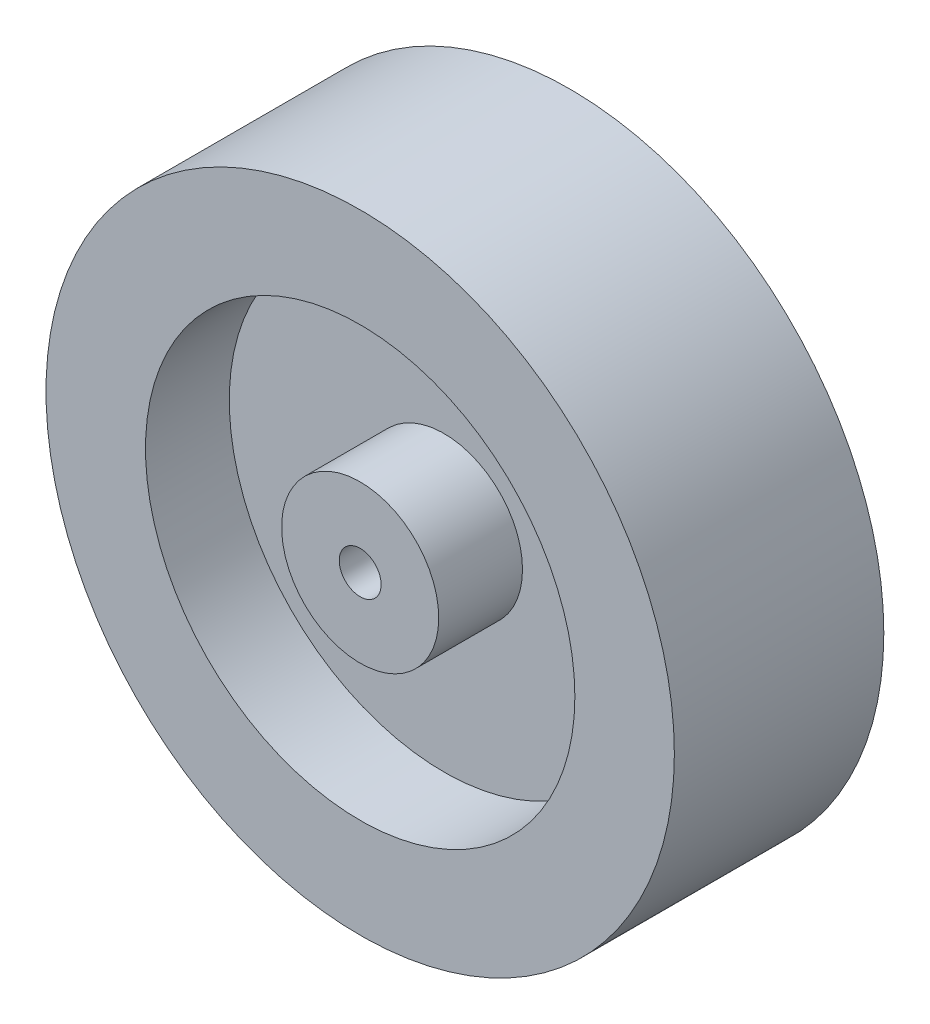
SolidWorks part; units mm, degrees
material "AISI 1020"
ref_plane "Plano frontal" through (0, 0, 0) normal (0, 0, 1) x (1, 0, 0)
ref_plane "Plano superior" through (0, 0, 0) normal (0, 1, 0) x (1, 0, 0)
ref_plane "Plano direito" through (0, 0, 0) normal (1, 0, 0) x (0, 0, -1)
sketch "Esboço1" plane through (0, 0, 0) normal (0, 0, 1) x (1, 0, 0)
  circle A0 centre (0, 0) radius 15
  circle A1 centre (0, 0) radius 1
  dimension "D1" = 30
  dimension "D2" = 2
extrude "Ressalto-extrusão1" add sketch "Esboço1" along normal blind 10
sketch "Esboço2" plane through (0, 0, 10) normal (0, 0, 1) x (1, 0, 0)
  circle A0 centre (0, 0) radius 3.75
  circle A1 centre (0, 0) radius 10.25
  dimension "D1" = 7.5
  dimension "D2" = 6.5
extrude "Corte-extrusão1" cut sketch "Esboço2" against normal blind 4
